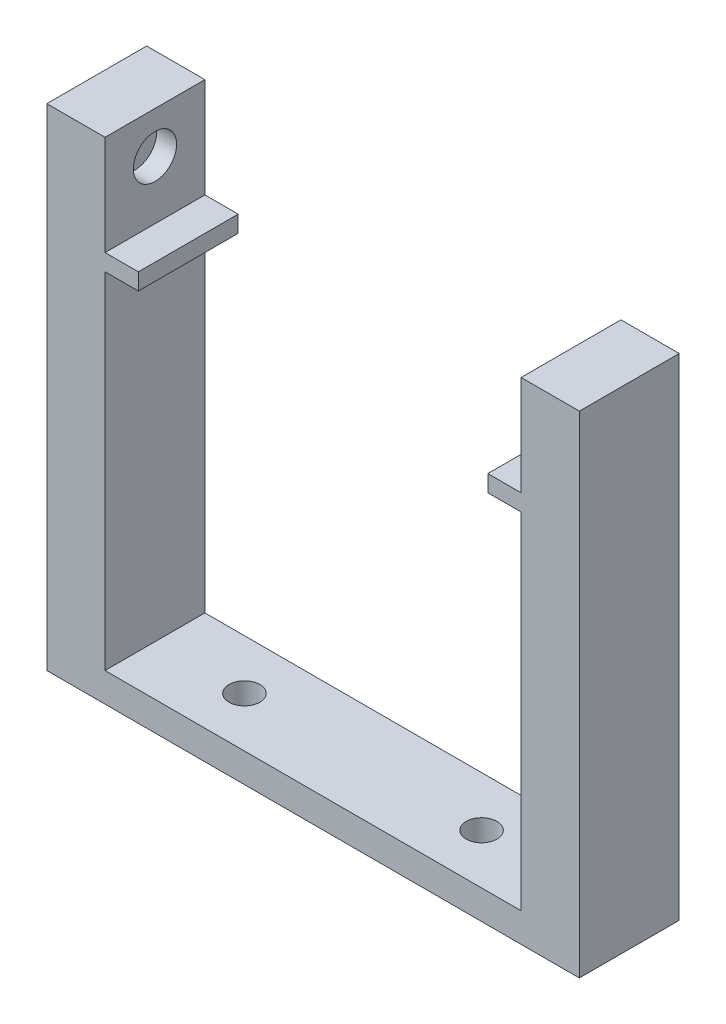
SolidWorks part; units mm, degrees
ref_plane "Front Plane" through (0, 0, 0) normal (0, 0, 1) x (1, 0, 0)
ref_plane "Top Plane" through (0, 0, 0) normal (0, 1, 0) x (1, 0, 0)
ref_plane "Right Plane" through (0, 0, 0) normal (1, 0, 0) x (0, 0, -1)
sketch "Sketch1" plane through (0, 0, 0) normal (0, 0, 1) x (1, 0, 0)
  line L1 (0, 0) -> (64, 0)
  line L2 (0, 0) -> (0, 59)
  line L3 (0, 59) -> (64, 59)
  line L4 (64, 0) -> (64, 59)
  line L8 (0, 59) -> (64, 0) construction
  line L10 (7, 3.5) -> (57, 3.5)
  line L11 (7, 3.5) -> (7, 55.5)
  line L12 (7, 55.5) -> (57, 55.5)
  line L13 (57, 3.5) -> (57, 55.5)
  line L14 (7, 3.5) -> (57, 55.5) construction
  line L15 (7, 55.5) -> (57, 3.5) construction
  point P5 (32, 29.5)
  dimension "D2" = 59
  dimension "D1" = 7
  dimension "D3" = 3.5
  dimension "D4" = 50
extrude "Boss-Extrude1" add sketch "Sketch1" along normal blind 12
sketch "Sketch2" plane through (0, 59, 0) normal (0, 1, 0) x (1, 0, 0)
  line L0 (18, -9.7) -> (46, -9.7) construction
  line L1 (32, 0) -> (32, -12) construction
  line L2 (64, 0) -> (0, 0) construction
  line L3 (64, -12) -> (0, -12) construction
  circle A0 centre (18, -9.7) radius 1.85
  circle A1 centre (46, -9.7) radius 1.85
  circle A2 centre (32, -9.7) radius 1.85
  point P11 (32, -6)
  dimension "D1" = 3.7
  dimension "D3" = 3.7
  dimension "D2" = 14
  dimension "D4" = 3.7
extrude "Cut-Extrude1" cut sketch "Sketch2" against normal blind 10
sketch "Sketch3" plane through (0, 0, 0) normal (0, -1, 0) x (1, 0, 0)
  line L0 (32, 0) -> (32, 12) construction
  line L1 (0, 0) -> (64, 0) construction
  line L2 (0, 12) -> (64, 12) construction
  line L3 (32, 6) -> (17.75, 6) construction
  circle A0 centre (17.75, 6) radius 1.85
  circle A1 centre (46.25, 6) radius 1.85
  dimension "D1" = 3.7
  dimension "D2" = 14.25
extrude "Cut-Extrude2" cut sketch "Sketch3" against normal blind 10
sketch "Sketch4" plane through (0, 59, 0) normal (0, 1, 0) x (1, 0, 0)
  line L0 (7, -12) -> (7, 0) construction
  line L1 (57, -12) -> (57, 0) construction
  line L2 (7, -12) -> (7, 0)
  line L3 (57, -12) -> (57, 0)
  line L8 (64, 0) -> (0, 0)
  line L9 (0, 0) -> (0, -12)
  line L10 (0, -12) -> (64, -12)
  line L11 (64, -12) -> (64, 0)
  line L12 (64, 0) -> (0, 0)
  line L13 (0, 0) -> (0, -12)
  line L14 (0, -12) -> (64, -12)
  line L15 (64, -12) -> (64, 0)
  circle M5 centre (18, -9.7) radius 1.85
  circle M6 centre (46, -9.7) radius 1.85
  circle M7 centre (32, -9.7) radius 1.85
  line M8 (64, 0) -> (0, 0)
  line M10 (0, -12) -> (64, -12)
  dimension "D1" = 0
extrude "Cut-Extrude4" cut sketch "Sketch4" against normal blind 10 contours L3 L2 M10 M8 M6 M7 M5 | L12 L13 L14 L15
sketch "Sketch6" plane through (7, 0, 0) normal (1, 0, 0) x (0, 0, -1)
  line L0 (-6, 59) -> (-6, 40.1234) construction
  line L1 (-12, 59) -> (0, 59) construction
  circle A0 centre (-6, 54) radius 2.6
  dimension "D2" = 5.2
  dimension "D1" = 5
extrude "Cut-Extrude5" cut sketch "Sketch6" against normal blind 2.4
ref_plane "Plane1" through (32, 0, 0) normal (-1, 0, 0) x (0, 0, 1)
mirror "Mirror1" about plane through (32, 0, 0) normal (-1, 0, 0) of "Cut-Extrude5"
sketch "Sketch7" plane through (57, 0, 0) normal (-1, 0, 0) x (0, 0, 1)
  line L1 (0, 47) -> (12, 47)
  line L2 (0, 47) -> (0, 45)
  line L3 (0, 45) -> (12, 45)
  line L4 (12, 47) -> (12, 45)
  line L6 (0, 3.5) -> (0, 59) construction
  line L7 (12, 3.5) -> (12, 59) construction
  line L8 (12, 59) -> (0, 59) construction
  dimension "D1" = 2
  dimension "D2" = 12
  dimension "D3" = 12
extrude "Boss-Extrude2" add sketch "Sketch7" along normal blind 4
mirror "Mirror2" about plane through (32, 0, 0) normal (-1, 0, 0) of "Boss-Extrude2"
